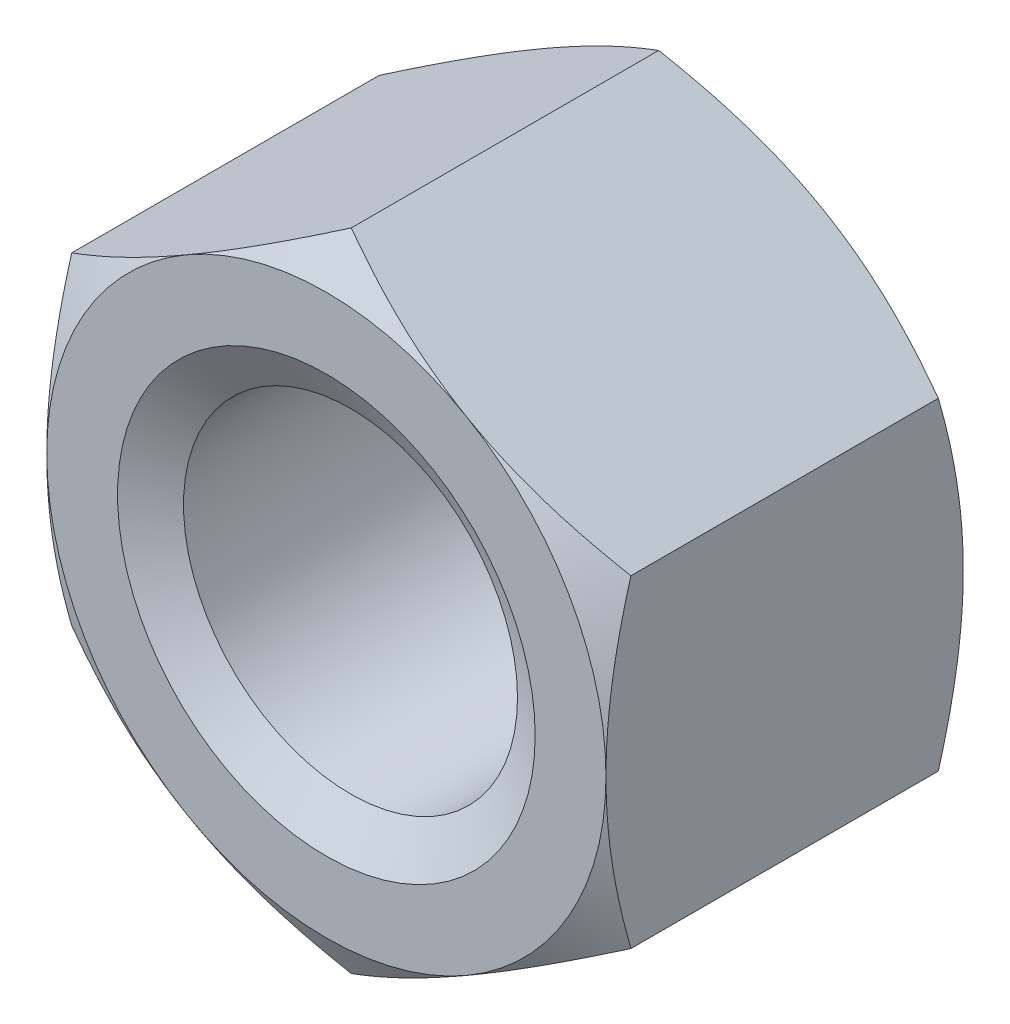
SolidWorks part; units mm, degrees
ref_plane "前视基准面" through (0, 0, 0) normal (0, 0, 1) x (1, 0, 0)
ref_plane "上视基准面" through (0, 0, 0) normal (0, 1, 0) x (1, 0, 0)
ref_plane "右视基准面" through (0, 0, 0) normal (1, 0, 0) x (0, 0, -1)
sketch "草图1" plane through (0, 0, 0) normal (1, 0, 0) x (0, 0, -1)
  line L0 (0, 13.375) -> (0, -13.375) construction
  line L1 (0, 0) -> (14.8, 0) construction
  line L2 (0, 0) -> (0, 13.375)
  line L3 (0, 13.375) -> (14.8, 13.375)
  line L4 (14.8, 13.375) -> (14.8, 0)
  line L5 (0, 8) -> (14.8, 8)
  line L6 (0, 6.9175) -> (14.8, 6.9175)
  line L7 (14, 13.375) -> (14, 0)
  line L8 (0, 12) -> (0.7939, 13.375)
  line L9 (0, 8) -> (0.625, 6.9175)
  line L10 (0, -8) -> (0.625, -6.9175)
  line L11 (14, 11.25) -> (14.8, 11.25)
  point P5 (3.5, 0)
  point P10 (12.8, 0)
  point P22 (0, 17.3)
  dimension "e" = 26.75
  dimension "m" = 14.8
  dimension "mw" = 11.3
  dimension "D" = 16
  dimension "P" = 2
  dimension "D81" = 13.835
  dimension "c" = 0.8
  dimension "β" = 30
  dimension "s" = 24
  dimension "θ" = 120
  dimension "dw" = 22.5
  dimension "da" = 17.3
sketch "草图2" plane through (0, 0, 0) normal (0, 0, 1) x (1, 0, 0)
  line L1 (0, 13.375) -> (-11.5831, 6.6875)
  line L2 (-11.5831, 6.6875) -> (-11.5831, -6.6875)
  line L3 (-11.5831, -6.6875) -> (0, -13.375)
  line L4 (0, -13.375) -> (11.5831, -6.6875)
  line L5 (11.5831, -6.6875) -> (11.5831, 6.6875)
  line L6 (11.5831, 6.6875) -> (0, 13.375)
  circle A0 centre (0, 0) radius 11.5831 construction
  circle A1 centre (0, 0) radius 6.9175
sketch "草图3" plane through (0, 0, 0) normal (0, 0, 1) x (1, 0, 0)
  line L0 (0, 13.375) -> (-11.5831, 6.6875) construction
  line L1 (11.5831, 6.6875) -> (0, 13.375) construction
  line L2 (11.5831, -6.6875) -> (11.5831, 6.6875) construction
  line L3 (0, -13.375) -> (11.5831, -6.6875) construction
  line L4 (-11.5831, -6.6875) -> (0, -13.375) construction
  line L5 (-11.5831, 6.6875) -> (-11.5831, -6.6875) construction
  line L6 (0, 13.375) -> (-11.5831, 6.6875)
  line L7 (11.5831, 6.6875) -> (0, 13.375)
  line L8 (11.5831, -6.6875) -> (11.5831, 6.6875)
  line L9 (0, -13.375) -> (11.5831, -6.6875)
  line L10 (-11.5831, -6.6875) -> (0, -13.375)
  line L11 (-11.5831, 6.6875) -> (-11.5831, -6.6875)
  circle A0 centre (0, 0) radius 6.9175 construction
  circle A1 centre (0, 0) radius 6.9175
extrude "凸台-拉伸1" add sketch "草图3" against normal up to vertex (14.8 mm away) up to point (0, 0, -14.8)
cosmetic thread "装饰螺纹线1" parameters "D2"=16
sketch "草图4" plane through (0, 0, 0) normal (1, 0, 0) x (0, 0, -1)
  line L1 (0, 8.65) -> (1.0003, 6.9175)
  line L2 (0, 0) -> (14.8, 0) construction
  line L3 (0, 0) -> (14.8, 0) construction
  line L4 (7.4, 0) -> (7.4, 13.375) construction
  line L5 (0, 13.375) -> (14.8, 13.375) construction
  line L6 (1.0003, 6.9175) -> (1.0003, 0)
  line L7 (1.0003, 0) -> (0, 0)
  line L8 (0, 0) -> (0, 8.65)
  line L9 (14.8, 0) -> (14.8, 8.65)
  line L10 (13.7997, 0) -> (14.8, 0)
  line L11 (13.7997, 6.9175) -> (13.7997, 0)
  line L12 (14.8, 8.65) -> (13.7997, 6.9175)
  line L16 (0, 8) -> (0.625, 6.9175) construction
  line L17 (0, 6.9175) -> (14.8, 6.9175) construction
  dimension "D1" = 17.3
revolve "切除-旋转1" cut sketch "草图4" angle 360 mid plane about L3
sketch "草图5" plane through (0, 0, 0) normal (0, 0, 1) x (1, 0, 0)
  circle A0 centre (0, 0) radius 11.5831
  circle A1 centre (0, 0) radius 20.0625
  circle A2 centre (0, 0) radius 11.5831 construction
  dimension "D1" = 40.125
extrude "切除-拉伸1" cut sketch "草图5" against normal blind 2.96 draft 60
sketch "草图7" plane through (0, 0, -14.8) normal (0, 0, -1) x (-1, 0, 0)
  circle A1 centre (0, 0) radius 20.0625
  circle A2 centre (0, 0) radius 20.0625
  circle A3 centre (0, 0) radius 11.5831
  circle A4 centre (0, 0) radius 11.5831
  dimension "D1" = 0
  dimension "D2" = 0
extrude "切除-拉伸2" cut sketch "草图7" against normal blind 2.96 draft 60
sketch "草图6" [suppressed] plane through (0, 0, 0) normal (1, 0, 0) x (0, 0, -1)
  line L0 (1.3, 1.2) -> (1.1, 1.2)
  line L1 (1.1, 1.2) -> (1.1, 1.705)
  line L2 (1.1, 1.705) -> (1.3, 1.705)
  line L3 (1.3, 1.705) -> (1.3, 1.2)
  line L4 (0, 0) -> (1.3, 0) construction
  line L5 (0, 0) -> (1.3, 0) construction
revolve "切除-旋转2" [suppressed] cut sketch "草图6" angle 360 mid plane about L5
